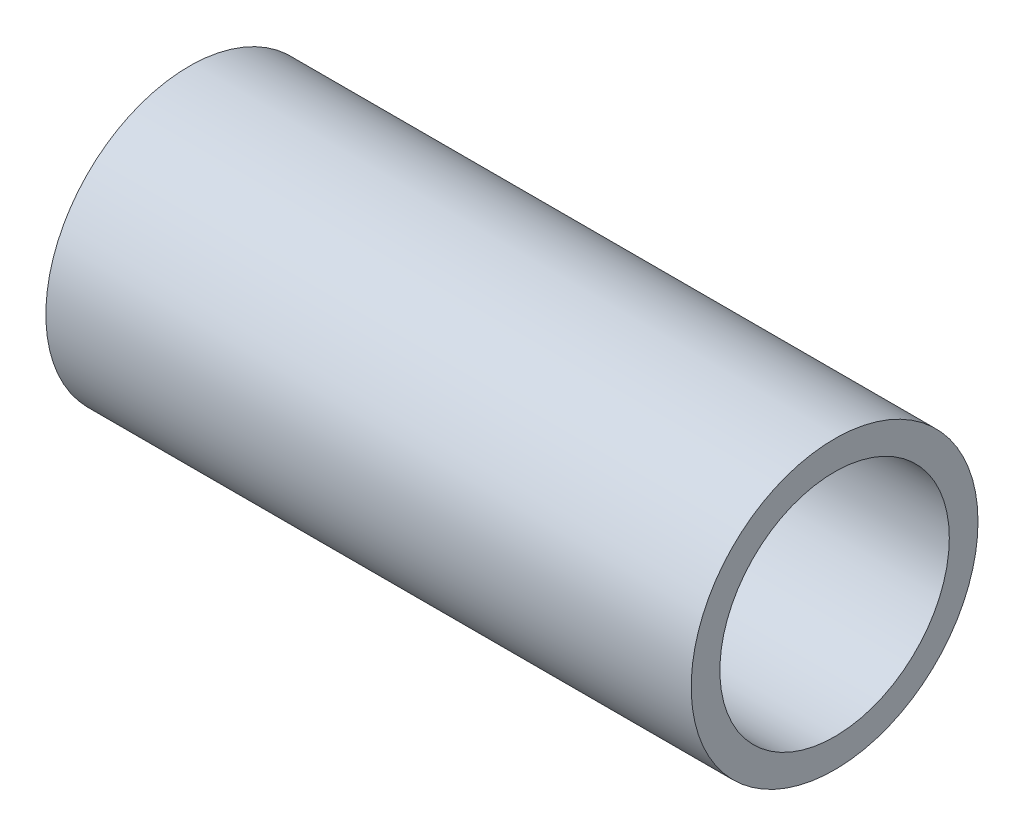
SolidWorks part; units mm, degrees
ref_plane "Front Plane" through (0, 0, 0) normal (0, 0, 1) x (1, 0, 0)
ref_plane "Top Plane" through (0, 0, 0) normal (0, 1, 0) x (1, 0, 0)
ref_plane "Right Plane" through (0, 0, 0) normal (1, 0, 0) x (0, 0, -1)
sketch "Sketch1" plane through (0, 0, 0) normal (1, 0, 0) x (0, 0, -1)
  circle A0 centre (0, 0) radius 3.175
  dimension "D1" = 6.35
extrude "Boss-Extrude1" add sketch "Sketch1" along normal blind 14.2875
hole_wizard "#10-24 Tapped Hole1" [suppressed] positions "Sketch2" profile "Sketch3" tap size "#10-24" standard "ANSI Inch"
sketch "Sketch2" plane through (209.55, 0, 0) normal (1, 0, 0) x (0, 0, -1)
  point P0 (0, 0)
sketch "Sketch3" plane through (209.55, 0, 0) normal (0, 1, 0) x (0, 0, -1)
  line L0 (0, 0) -> (0, 14.1499)
  line L1 (0, 14.1499) -> (2.413, 12.7)
  line L2 (2.413, 12.7) -> (2.413, 0)
  line L5 (2.413, 0) -> (0, 0)
  line L10 (0, 14.1499) -> (-2.413, 12.7) construction
  line L11 (0, -6.35) -> (0, 107.95) construction
  dimension "Tap Drill Dia." = 4.826
  dimension "Tap Drill Depth" = 12.7
  dimension "Drill Angle" = 118
cosmetic thread "Hole Thread3" [suppressed] parameters "D1"=9.652, "D2"=4.826
hole_wizard "#10-24 Tapped Hole2" [suppressed] positions "Sketch4" profile "Sketch5" tap size "#10-24" standard "ANSI Inch"
sketch "Sketch4" plane through (0, 0, 0) normal (-1, 0, 0) x (0, 0, 1)
  point P0 (0, 0)
sketch "Sketch5" plane through (0, 0, 0) normal (0, 1, 0) x (0, 0, 1)
  line L0 (0, 0) -> (0, 14.4039)
  line L1 (0, 14.4039) -> (2.413, 12.954)
  line L2 (2.413, 12.954) -> (2.413, 0)
  line L5 (2.413, 0) -> (0, 0)
  line L10 (0, 14.4039) -> (-2.413, 12.954) construction
  line L11 (0, -6.35) -> (0, 107.95) construction
  dimension "Tap Drill Dia." = 4.826
  dimension "Tap Drill Depth" = 12.954
  dimension "Drill Angle" = 118
cosmetic thread "Hole Thread2" [suppressed] parameters "D1"=9.652, "D2"=4.826
sketch "Sketch6" plane through (14.2875, 0, 0) normal (1, 0, 0) x (0, 0, -1)
  circle A0 centre (0, 0) radius 2.54
  dimension "D1" = 5.08
extrude "Cut-Extrude1" cut sketch "Sketch6" against normal through all
